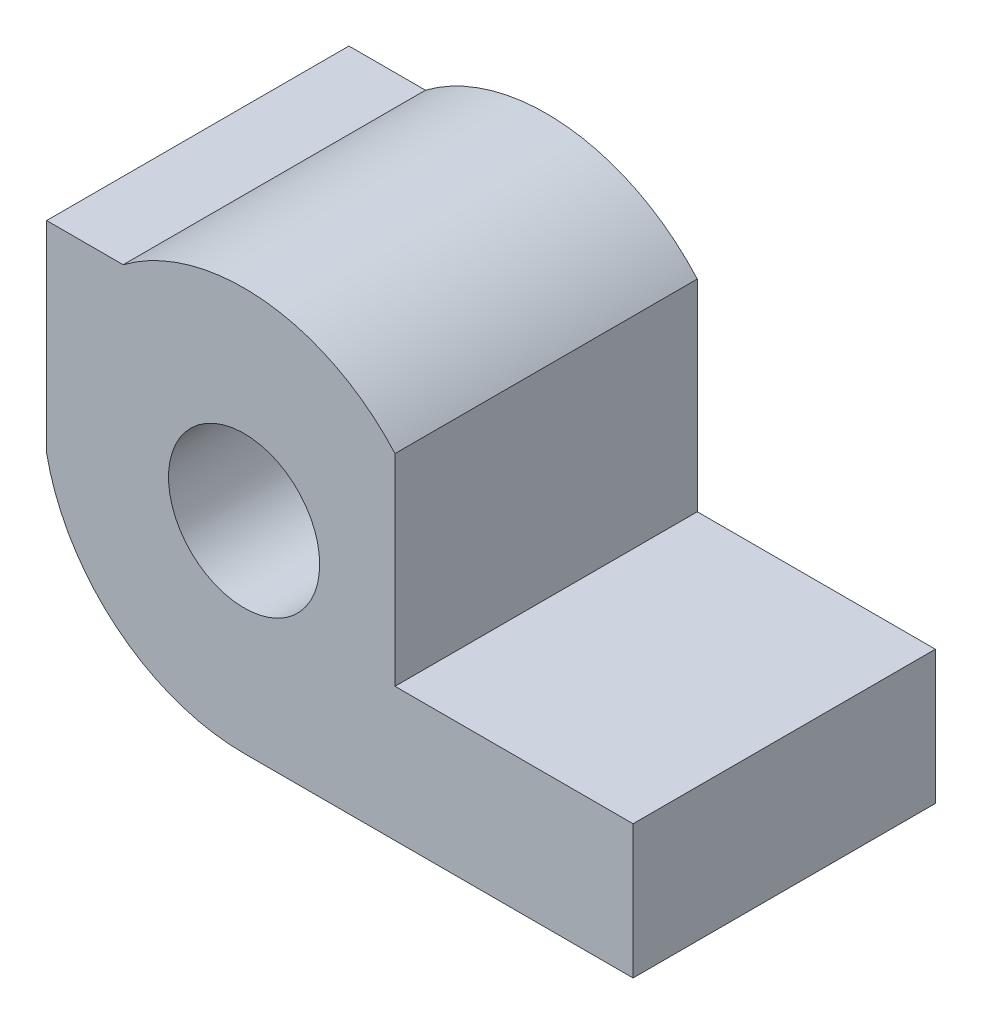
SolidWorks part; units mm, degrees
ref_plane "Front Plane" through (0, 0, 0) normal (0, 0, 1) x (1, 0, 0)
ref_plane "Top Plane" through (0, 0, 0) normal (0, 1, 0) x (1, 0, 0)
ref_plane "Right Plane" through (0, 0, 0) normal (1, 0, 0) x (0, 0, -1)
sketch "Sketch1" plane through (0, 0, 0) normal (0, 0, 1) x (1, 0, 0)
  line L0 (8.3196, -4) -> (0.5996, -4)
  line L1 (-3.3196, 3.2) -> (-3.3196, -0.8)
  line L2 (8.3196, -1.3485) -> (8.3196, -4)
  line L4 (3.5945, 2.6515) -> (3.5945, -1.3485)
  line L6 (3.5945, -1.3485) -> (8.3196, -1.3485)
  line L8 (-3.3196, 3.2) -> (-1.8004, 3.2)
  circle A0 centre (0.5996, 0) radius 1.5
  arc A1 (3.5945, 2.6515) -> (-1.8004, 3.2) centre (0.5996, 0) ccw
  arc A2 (-3.3196, -0.8) -> (0.5996, -4) centre (0.5996, 0) ccw
  dimension "D1" = 3
  dimension "D3" = 4
  dimension "D2" = 7.72
  dimension "D4" = 4
  dimension "D5" = 2.6515
  dimension "D6" = 1.5192
  dimension "D7" = 4
extrude "Boss-Extrude1" add sketch "Sketch1" along normal blind 6
